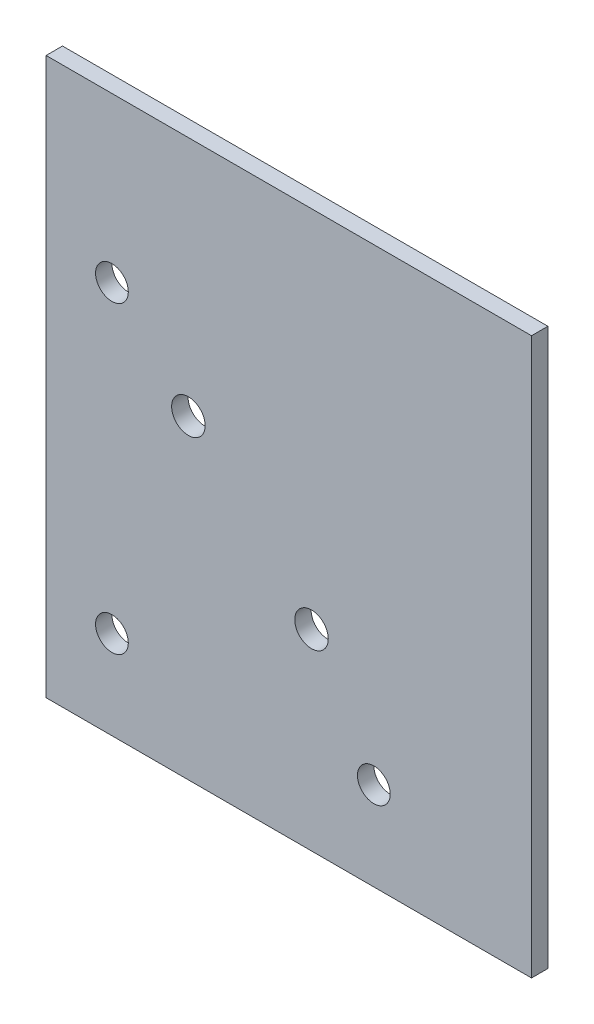
SolidWorks part; units mm, degrees
ref_plane "Front Plane" through (0, 0, 0) normal (0, 0, 1) x (1, 0, 0)
ref_plane "Top Plane" through (0, 0, 0) normal (0, 1, 0) x (1, 0, 0)
ref_plane "Right Plane" through (0, 0, 0) normal (1, 0, 0) x (0, 0, -1)
sketch "Sketch1" plane through (0, 0, 0) normal (0, 0, 1) x (1, 0, 0)
  line L1 (5.1833, 100.7604) -> (-88.9667, 100.7604)
  line L2 (5.1833, 100.7604) -> (5.1833, 208.6503)
  line L3 (5.1833, 208.6503) -> (-88.9667, 208.6503)
  line L4 (-88.9667, 100.7604) -> (-88.9667, 208.6503)
  line L5 (-23.2675, 150.6967) -> (-48.6675, 150.6967) construction
  line L6 (-48.6675, 201.4967) -> (-48.6675, 150.6967) construction
  circle A3 centre (-76.2, 117.9286) radius 3.175
  circle A4 centre (-25.4, 117.9286) radius 3.175
  circle A5 centre (-76.2, 176.8929) radius 3.175
  circle A6 centre (-61.3675, 161.8727) radius 3.2512
  circle A7 centre (-37.4915, 137.9967) radius 3.2512
  dimension "D1" = 6.5024
  dimension "D2" = 12.7
  dimension "D3" = 11.176
  dimension "D4" = 12.7
  dimension "D5" = 11.176
extrude "Boss-Extrude1" add sketch "Sketch1" along normal blind 3.175
equation "\"80/20 to Center Hole\"= .64in"
equation "\"80/20 from Edge\"= 0.5in"
